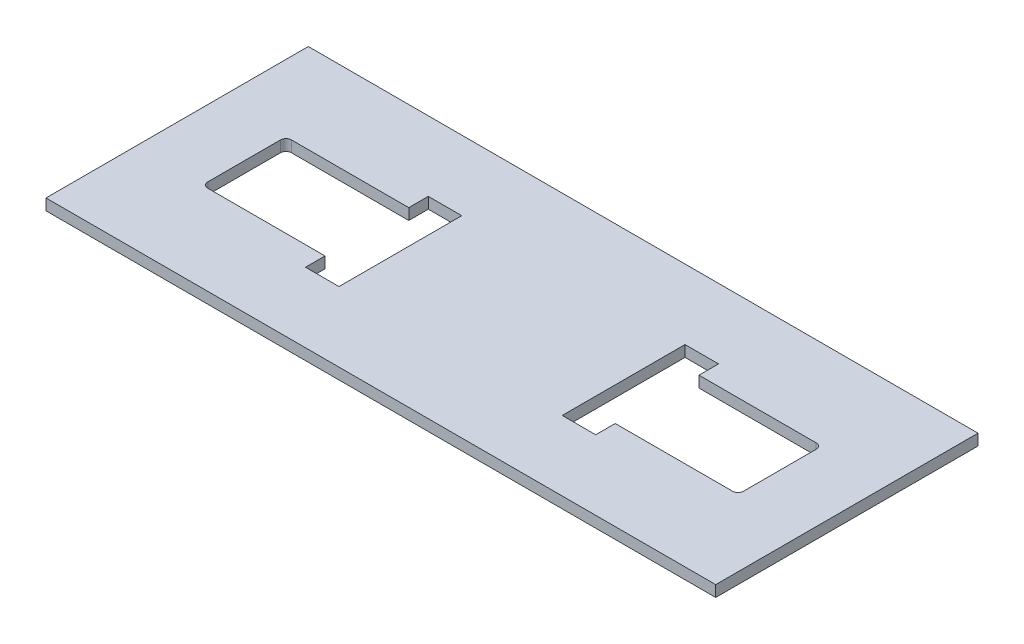
SolidWorks part; units mm, degrees
material "6061 Alloy"
ref_plane "Front Plane" through (0, 0, 0) normal (0, 0, 1) x (1, 0, 0)
ref_plane "Top Plane" through (0, 0, 0) normal (0, 1, 0) x (1, 0, 0)
ref_plane "Right Plane" through (0, 0, 0) normal (1, 0, 0) x (0, 0, -1)
sketch "Sketch1" plane through (0, 0, 0) normal (0, 1, 0) x (1, 0, 0)
  line L0 (381, 0) -> (381, 149.225)
  line L1 (0, 0) -> (381, 0)
  line L3 (0, 149.225) -> (381, 149.225)
  line L5 (190.5, 0) -> (190.5, 149.225) construction
  line L6 (342.9, 95.25) -> (342.9, 53.975)
  line L7 (41.275, 98.425) -> (123.825, 98.425)
  line L8 (127, 95.25) -> (127, 53.975)
  line L9 (123.825, 50.8) -> (41.275, 50.8)
  line L13 (0, 0) -> (0, 149.225)
  line L15 (38.1, 95.25) -> (38.1, 53.975)
  line L16 (38.1, 98.425) -> (38.1, 149.225) construction
  line L17 (38.1, 50.8) -> (38.1, 0) construction
  line L18 (257.175, 50.8) -> (339.725, 50.8)
  line L19 (254, 95.25) -> (254, 53.975)
  line L20 (339.725, 98.425) -> (257.175, 98.425)
  line L21 (0, 74.6125) -> (381, 74.6125) construction
  arc A0 (127, 53.975) -> (123.825, 50.8) centre (123.825, 53.975) cw
  arc A1 (123.825, 98.425) -> (127, 95.25) centre (123.825, 95.25) cw
  arc A4 (38.1, 53.975) -> (41.275, 50.8) centre (41.275, 53.975) ccw
  arc A5 (38.1, 95.25) -> (41.275, 98.425) centre (41.275, 95.25) cw
  arc A6 (342.9, 95.25) -> (339.725, 98.425) centre (339.725, 95.25) ccw
  arc A7 (342.9, 53.975) -> (339.725, 50.8) centre (339.725, 53.975) cw
  arc A8 (257.175, 98.425) -> (254, 95.25) centre (257.175, 95.25) ccw
  arc A9 (254, 53.975) -> (257.175, 50.8) centre (257.175, 53.975) ccw
  point P22 (127, 50.8)
  point P25 (127, 98.425)
  point P37 (254, 98.425)
  point P38 (254, 50.8)
  dimension "D4" = 3.175
  dimension "D7" = 88.9
  dimension "D3" = 3.175
  dimension "D1" = 381
  dimension "D2" = 149.225
  dimension "D5" = 190.5
  dimension "D6" = 47.625
  dimension "D8" = 38.1
extrude "Boss-Extrude1" add sketch "Sketch1" along normal blind 6.35
sketch "Sketch5" plane through (0, 6.35, 0) normal (0, 1, 0) x (1, 0, 0)
  line L0 (381, 149.225) -> (0, 149.225) construction
  line L1 (0, 0) -> (381, 0) construction
  line L2 (0, 149.225) -> (0, 0) construction
  line L3 (190.5, 149.225) -> (190.5, 0) construction
  line L4 (0, 74.6125) -> (381, 74.6125) construction
  line L5 (381, 0) -> (381, 149.225) construction
  point P0 (19.05, 130.175)
  point P2 (19.05, 19.05)
  point P4 (19.05, 74.6125)
  point P5 (361.95, 19.05)
  point P10 (361.95, 74.6125)
  point P13 (361.95, 130.175)
  dimension "D1" = 19.05
  dimension "D2" = 19.05
  dimension "D3" = 19.05
sketch "Sketch9" plane through (0, 6.35, 0) normal (0, 1, 0) x (1, 0, 0)
  line L1 (107.95, 95.25) -> (127, 95.25)
  line L2 (107.95, 95.25) -> (107.95, 109.5375)
  line L3 (107.95, 109.5375) -> (127, 109.5375)
  line L4 (127, 95.25) -> (127, 109.5375)
  line L5 (127, 53.975) -> (127, 95.25) construction
  line L6 (127, 74.6125) -> (254, 74.6125) construction
  line L7 (254, 95.25) -> (254, 53.975) construction
  line L8 (190.5, 0) -> (190.5, 149.225) construction
  line L9 (0, 0) -> (381, 0) construction
  line L10 (381, 149.225) -> (0, 149.225) construction
  line L11 (107.95, 39.6875) -> (127, 39.6875)
  line L12 (127, 53.975) -> (127, 39.6875)
  line L13 (107.95, 53.975) -> (127, 53.975)
  line L14 (107.95, 53.975) -> (107.95, 39.6875)
  line L15 (273.05, 53.975) -> (273.05, 39.6875)
  line L16 (273.05, 53.975) -> (254, 53.975)
  line L17 (254, 53.975) -> (254, 39.6875)
  line L18 (273.05, 39.6875) -> (254, 39.6875)
  line L19 (273.05, 109.5375) -> (254, 109.5375)
  line L20 (254, 95.25) -> (254, 109.5375)
  line L21 (273.05, 95.25) -> (254, 95.25)
  line L22 (273.05, 95.25) -> (273.05, 109.5375)
  line L23 (123.825, 98.425) -> (41.275, 98.425) construction
  dimension "D1" = 11.1125
  dimension "D2" = 19.05
extrude "Cut-Extrude1" cut sketch "Sketch9" against normal blind 7.62
